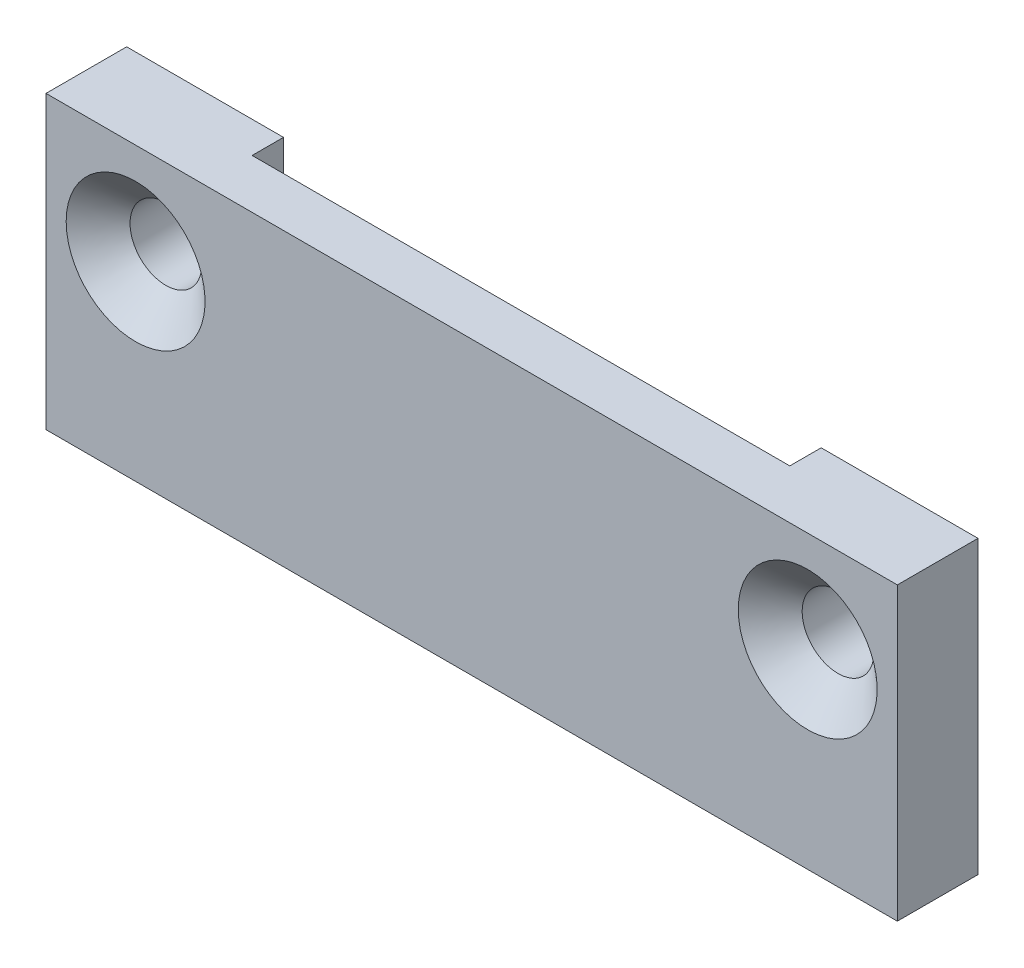
SolidWorks part; units mm, degrees
ref_plane "Front Plane" through (0, 0, 0) normal (0, 0, 1) x (1, 0, 0)
ref_plane "Top Plane" through (0, 0, 0) normal (0, 1, 0) x (1, 0, 0)
ref_plane "Right Plane" through (0, 0, 0) normal (1, 0, 0) x (0, 0, -1)
sketch "Sketch1" plane through (0, 0, 0) normal (0, 0, 1) x (1, 0, 0)
  line L0 (0, 6.5) -> (0, -6.5) construction
  line L1 (19, 6.5) -> (-19, 6.5)
  line L2 (19, 6.5) -> (19, -6.5)
  line L3 (19, -6.5) -> (-19, -6.5)
  line L4 (-19, 6.5) -> (-19, -6.5)
  line L5 (19, 6.5) -> (-19, -6.5) construction
  line L6 (19, -6.5) -> (-19, 6.5) construction
  circle A0 centre (-15, 2) radius 1.6
  circle A1 centre (15, 2) radius 1.6
  point P0 (0, 0)
  dimension "D2" = 3.2
  dimension "D1" = 38
  dimension "D3" = 15
  dimension "D4" = 4.5
  dimension "D5" = 13
extrude "Boss-Extrude1" add sketch "Sketch1" along normal blind 3.6
sketch "Sketch2" plane through (0, 6.5, 0) normal (0, 1, 0) x (1, 0, 0)
  line L0 (-12, 0) -> (-12, -1.4)
  line L1 (19, 0) -> (-19, 0) construction
  line L2 (-12, -1.4) -> (12, -1.4)
  line L3 (12, -1.4) -> (12, 0)
  line L5 (-12, 0) -> (12, 0)
  point P4 (0, 0)
  dimension "D1" = 12
  dimension "D2" = 12
  dimension "D3" = 1.4
extrude "Cut-Extrude1" cut sketch "Sketch2" against normal through all
chamfer "Chamfer1" distance 1.5 angle 42 2 edges at (13.4, 2, 3.6) (-13.4, 2, 3.6)
sketch "Sketch3" plane through (0, 0, 3.6) normal (0, 0, 1) x (1, 0, 0)
  line L0 (-12, 6.5) -> (-10.8453, 4.5)
  line L1 (19, 6.5) -> (-19, 6.5) construction
  line L2 (-10.8453, 4.5) -> (10.8453, 4.5)
  line L3 (10.8453, 4.5) -> (12, 6.5)
  line L4 (-19, 6.5) -> (-19, -6.5) construction
  line L5 (19, -6.5) -> (19, 6.5) construction
  line L6 (-12, 6.5) -> (12, 6.5)
  dimension "D1" = 7
  dimension "D2" = 7
  dimension "D3" = 120
  dimension "D4" = 120
  dimension "D5" = 2
extrude "Cut-Extrude2" [suppressed] cut sketch "Sketch3" against normal blind 3.6
